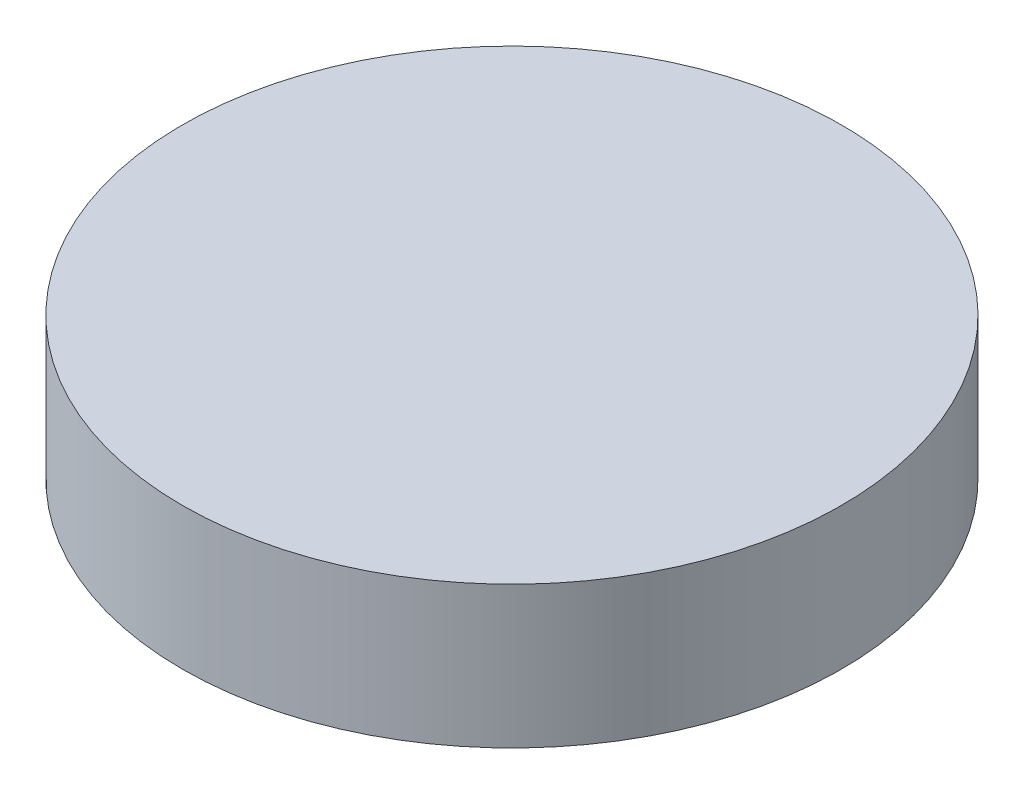
SolidWorks part; units mm, degrees
ref_plane "前视基准面" through (0, 0, 0) normal (0, 0, 1) x (1, 0, 0)
ref_plane "上视基准面" through (0, 0, 0) normal (0, 1, 0) x (1, 0, 0)
ref_plane "右视基准面" through (0, 0, 0) normal (1, 0, 0) x (0, 0, -1)
sketch "草图1" plane through (0, 0, 0) normal (0, 1, 0) x (1, 0, 0)
  circle A0 centre (0, 0) radius 39.5
extrude "凸台-拉伸1" add sketch "草图1" along normal blind 17
